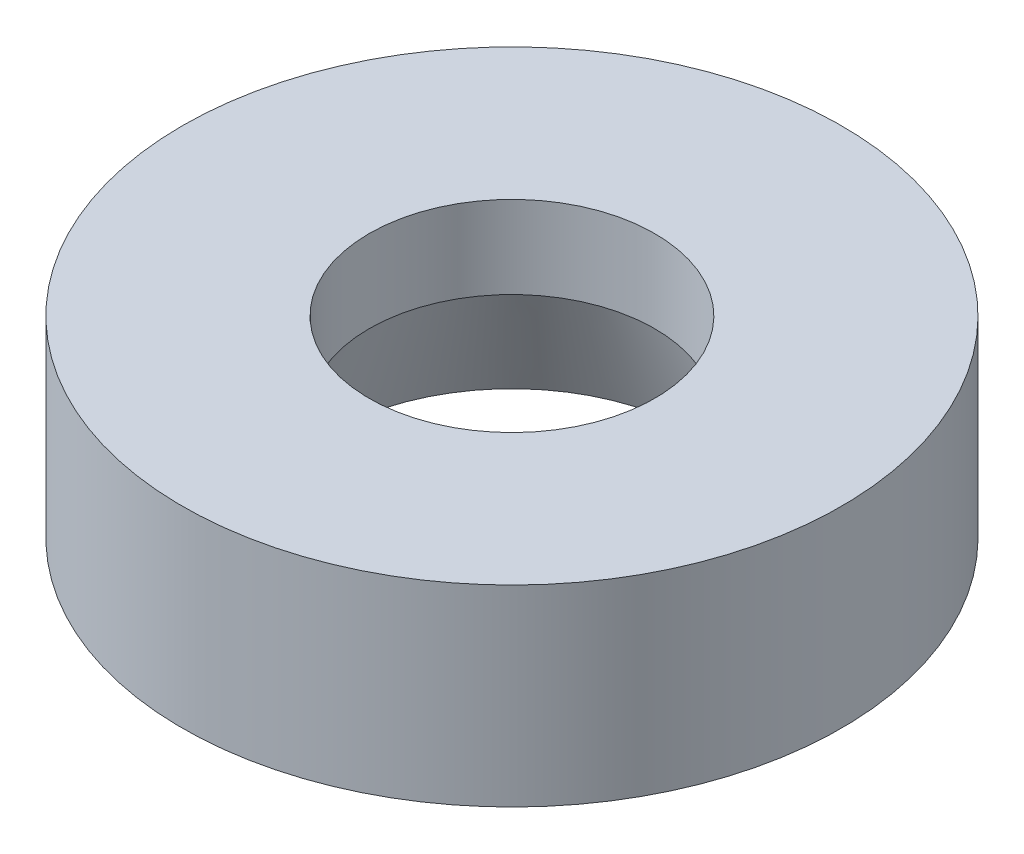
SolidWorks part; units mm, degrees
ref_plane "Płaszczyzna przednia" through (0, 0, 0) normal (0, 0, 1) x (1, 0, 0)
ref_plane "Płaszczyzna górna" through (0, 0, 0) normal (0, 1, 0) x (1, 0, 0)
ref_plane "Płaszczyzna prawa" through (0, 0, 0) normal (1, 0, 0) x (0, 0, -1)
sketch "Szkic1" plane through (0, 0, 0) normal (0, 0, 1) x (1, 0, 0)
  line L0 (0, 20.451) -> (0, -14.549) construction
  line L1 (-60, 20.451) -> (-60, -14.549)
  line L2 (-60, 20.451) -> (-26, 20.451)
  line L6 (-26, 20.451) -> (-26, 5.451)
  line L7 (-26, 5.451) -> (-33.2794, -14.549)
  line L8 (-26, 5.451) -> (-26, -20.656) construction
  line L9 (-33.2794, -14.549) -> (-60, -14.549)
  dimension "D1" = 60
  dimension "D2" = 20
  dimension "D3" = 15
  dimension "D4" = 35
revolve "Obrót1" add sketch "Szkic1" angle 360 about L0
